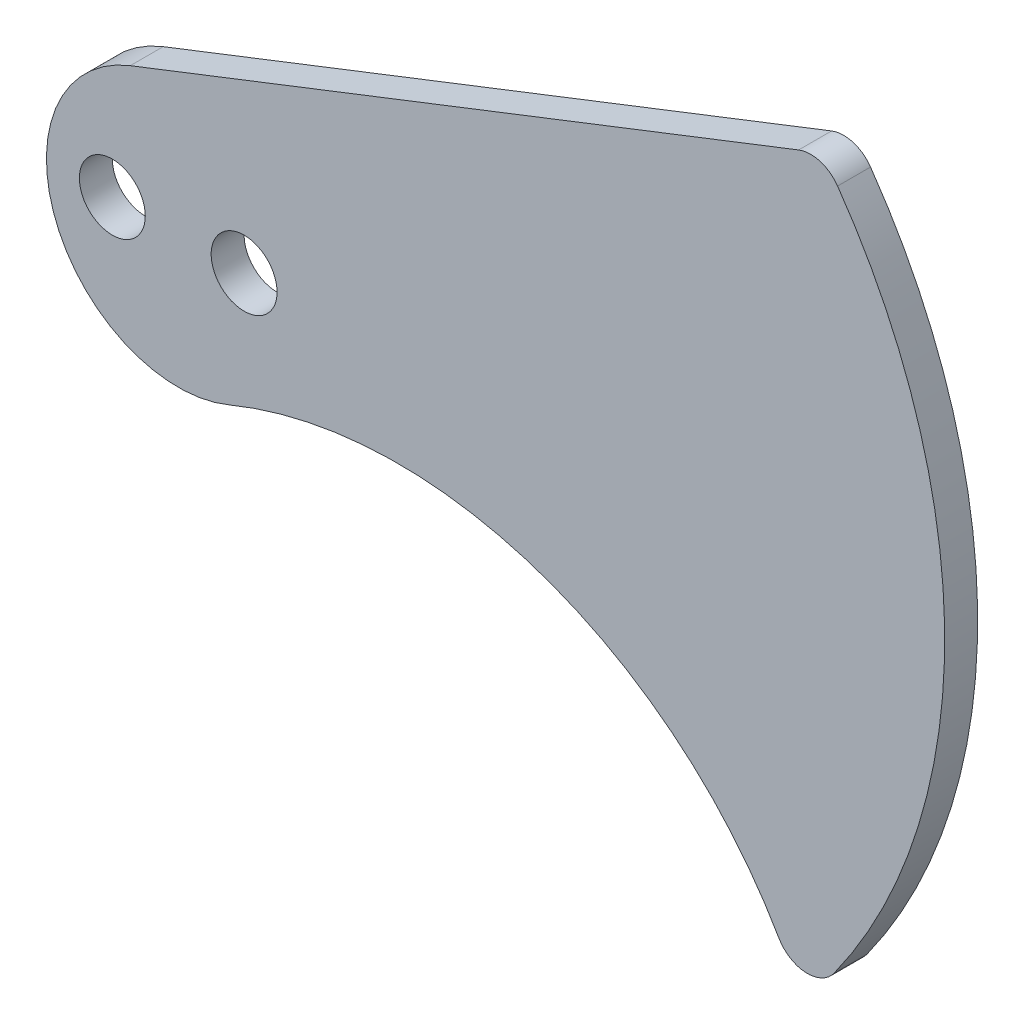
SolidWorks part; units mm, degrees
material "1023 Carbon Steel Sheet (SS)"
ref_plane "Front Plane" through (0, 0, 0) normal (1, 0, 0) x (0, 1, 0)
ref_plane "Top Plane" through (0, 0, 0) normal (0, 0, 1) x (0, 1, 0)
ref_plane "Right Plane" through (0, 0, 0) normal (0, 1, 0) x (-1, 0, 0)
sketch "Sketch1" plane through (0, 0, 0) normal (0, 0, 1) x (0, 1, 0)
  line L0 (-0.8232, 4.3679) -> (22.9591, -56.4873)
  arc A0 (-0.8232, 4.3679) -> (-23.0769, -4.6154) centre (-12, 0) ccw
  arc A1 (-23.0769, -4.6154) -> (-40.0743, -54.6838) centre (-60, -20) cw
  arc A2 (-40.3271, -59.7238) -> (21.8876, -60.0353) centre (-9, -16) ccw
  circle A3 centre (-12, 6) radius 3
  circle A4 centre (-12, -6) radius 3
  arc A5 (21.8876, -60.0353) -> (22.9591, -56.4873) centre (20.1649, -57.5793) ccw
  arc A6 (-40.0743, -54.6838) -> (-40.3271, -59.7238) centre (-38.5799, -57.2851) ccw
  point P15 (23.7973, -58.6321)
  dimension "D1" = 12
  dimension "D2" = 40
  dimension "D3" = 53.7881
  dimension "D10" = 6
  dimension "D11" = 6
  dimension "D15" = 3
  dimension "D4" = 63
  dimension "D5" = 12
  dimension "D6" = 16
  dimension "D7" = 9
  dimension "D8" = 60
  dimension "D9" = 20
  dimension "D12" = 12
  dimension "D13" = 6
  dimension "D14" = 6
extrude "Boss-Extrude1" add sketch "Sketch1" along normal blind 3
